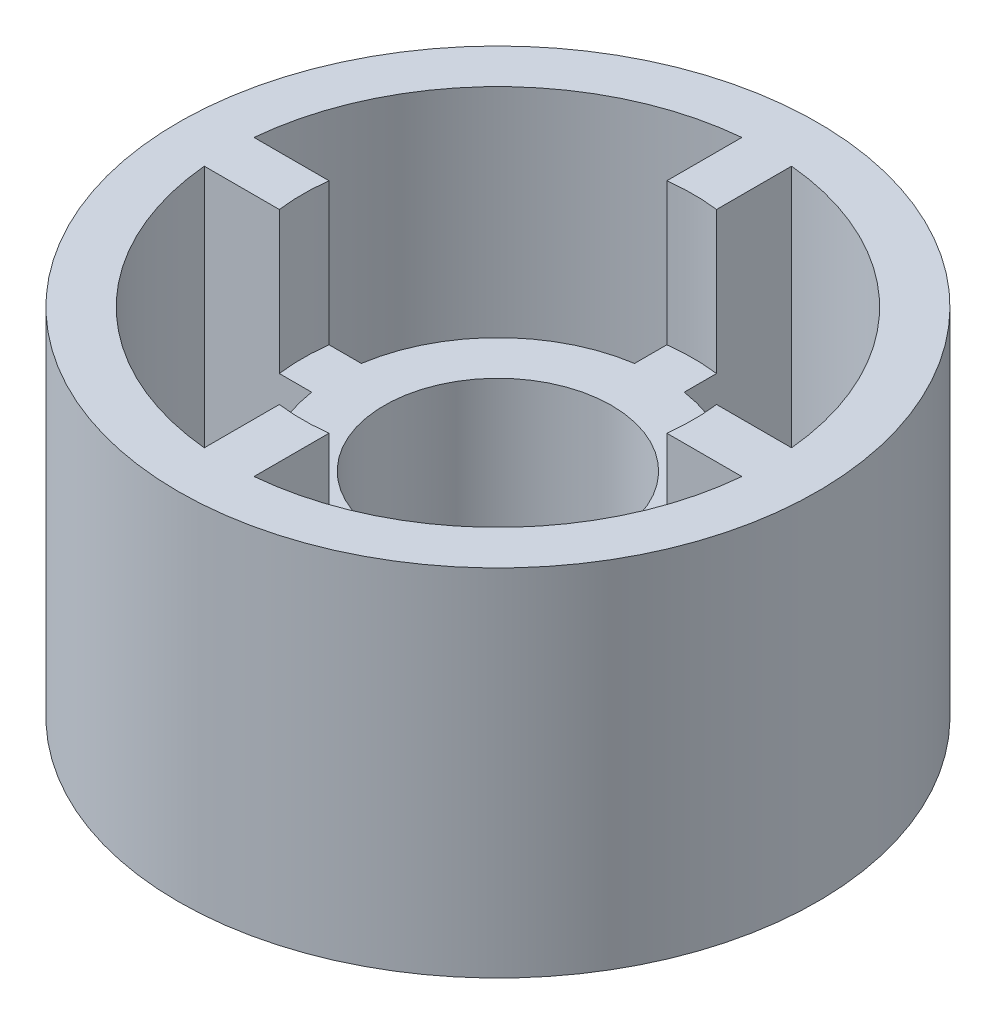
SolidWorks part; units mm, degrees
ref_plane "前视基准面" through (0, 0, 0) normal (0, 0, 1) x (1, 0, 0)
ref_plane "上视基准面" through (0, 0, 0) normal (0, 1, 0) x (1, 0, 0)
ref_plane "右视基准面" through (0, 0, 0) normal (1, 0, 0) x (0, 0, -1)
sketch "草图1" plane through (0, 0, 0) normal (0, 1, 0) x (1, 0, 0)
  line L0 (0, 0) -> (4.5796, 0) construction
  line L1 (2.2732, 0.35) -> (3.7838, 0.35)
  line L2 (2.2732, -0.35) -> (3.7838, -0.35)
  line L3 (0.35, -2.2732) -> (0.35, -3.7838)
  line L4 (-0.35, -2.2732) -> (-0.35, -3.7838)
  line L5 (-2.2732, -0.35) -> (-3.7838, -0.35)
  line L6 (-2.2732, 0.35) -> (-3.7838, 0.35)
  line L7 (-0.35, 2.2732) -> (-0.35, 3.7838)
  line L8 (0.35, 2.2732) -> (0.35, 3.7838)
  circle A0 centre (0, 0) radius 1.6
  arc A1 (2.2732, 0.35) -> (0.35, 2.2732) centre (0, 0) ccw
  arc A2 (3.7838, 0.35) -> (0.35, 3.7838) centre (0, 0) ccw
  circle A3 centre (0, 0) radius 4.5
  arc A4 (-0.35, 2.2732) -> (-2.2732, 0.35) centre (0, 0) ccw
  arc A5 (-0.35, 3.7838) -> (-3.7838, 0.35) centre (0, 0) ccw
  arc A6 (-3.7838, -0.35) -> (-0.35, -3.7838) centre (0, 0) ccw
  arc A7 (-2.2732, -0.35) -> (-0.35, -2.2732) centre (0, 0) ccw
  arc A8 (0.35, -3.7838) -> (3.7838, -0.35) centre (0, 0) ccw
  arc A9 (0.35, -2.2732) -> (2.2732, -0.35) centre (0, 0) ccw
  point P26 (0, 0)
  dimension "D1" = 3.2
  dimension "D2" = 0.7
  dimension "D3" = 0.7
  dimension "D4" = 9
  dimension "D5" = 0.7
  dimension "D6" = 4
extrude "凸台-拉伸1" add sketch "草图1" along normal blind 5
sketch "草图2" plane through (0, 5, 0) normal (0, 1, 0) x (1, 0, 0)
  circle A0 centre (0, 0) radius 2.75
  dimension "D1" = 5.5
extrude "切除-拉伸1" cut sketch "草图2" against normal blind 2
